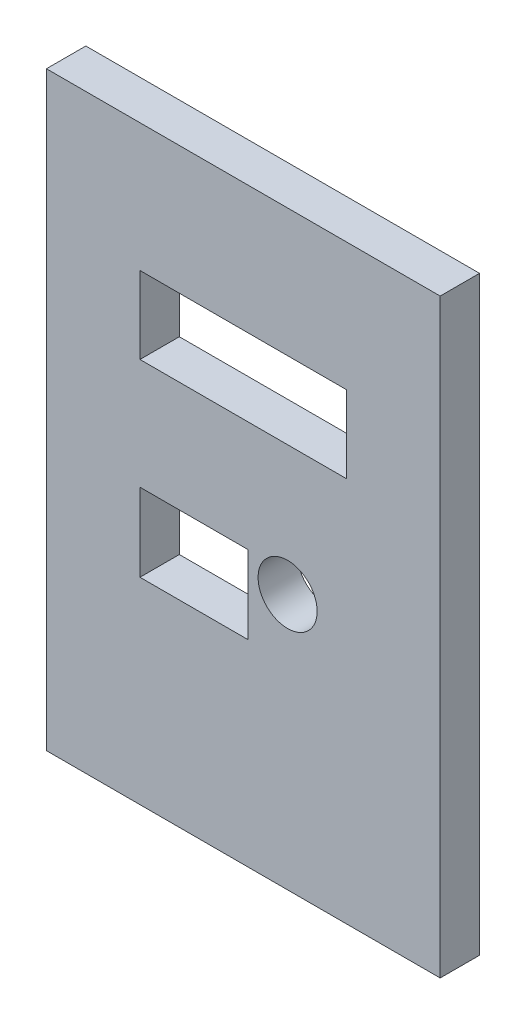
SolidWorks part; units mm, degrees
ref_plane "Front Plane" through (0, 0, 0) normal (0, 0, 1) x (1, 0, 0)
ref_plane "Top Plane" through (0, 0, 0) normal (0, 1, 0) x (1, 0, 0)
ref_plane "Right Plane" through (0, 0, 0) normal (1, 0, 0) x (0, 0, -1)
sketch "Sketch1" plane through (0, 0, 0) normal (0, 0, 1) x (1, 0, 0)
  line L1 (10, -15) -> (-10, -15)
  line L2 (10, -15) -> (10, 15)
  line L3 (10, 15) -> (-10, 15)
  line L4 (-10, -15) -> (-10, 15)
  line L5 (10, -15) -> (-10, 15) construction
  line L6 (10, 15) -> (-10, -15) construction
  point P0 (0, 0)
  dimension "D1" = 20
  dimension "D2" = 30
extrude "Boss-Extrude1" add sketch "Sketch1" along normal blind 2
sketch "Sketch2" plane through (0, 0, 2) normal (0, 0, 1) x (1, 0, 0)
  line L0 (0, 0) -> (0, 15) construction
  line L1 (10, 15) -> (-10, 15) construction
  line L2 (-10, -15) -> (10, -15) construction
  line L3 (5.25, -5) -> (-5.25, -5)
  line L4 (5.25, -5) -> (5.25, 8.5)
  line L5 (5.25, 8.5) -> (-5.25, 8.5)
  line L6 (-5.25, -5) -> (-5.25, 8.5)
  line L7 (5.25, -5) -> (-5.25, 8.5) construction
  line L8 (5.25, 8.5) -> (-5.25, -5) construction
  line L10 (5.25, 4.5846) -> (-5.25, 4.5846)
  line L11 (5.25, 4.5846) -> (5.25, 8.5)
  line L12 (5.25, 8.5) -> (-5.25, 8.5)
  line L13 (-5.25, 4.5846) -> (-5.25, 8.5)
  line L14 (5.25, 4.5846) -> (-5.25, 8.5) construction
  line L15 (5.25, 8.5) -> (-5.25, 4.5846) construction
  line L16 (0.25, -4.996) -> (-5.25, -4.996)
  line L17 (0.25, -4.996) -> (0.25, -1.0344)
  line L18 (0.25, -1.0344) -> (-5.25, -1.0344)
  line L19 (-5.25, -4.996) -> (-5.25, -1.0344)
  line L20 (0.25, -4.996) -> (-5.25, -1.0344) construction
  line L21 (0.25, -1.0344) -> (-5.25, -4.996) construction
  circle A0 centre (2.25, -2) radius 1.5
  point P5 (0, 1.75)
  point P12 (0, 6.5423)
  point P13 (-2.5, -3.0152)
  dimension "D4" = 3
  dimension "D1" = 10
  dimension "D2" = 13.5
  dimension "D3" = 10.5
  dimension "D5" = 3
  dimension "D6" = 3
  dimension "D7" = 5.5
extrude "Cut-Extrude1" cut sketch "Sketch2" against normal blind 10 contours L10 L4 L5 L6 | L17 L18 L6 L16 | A0
